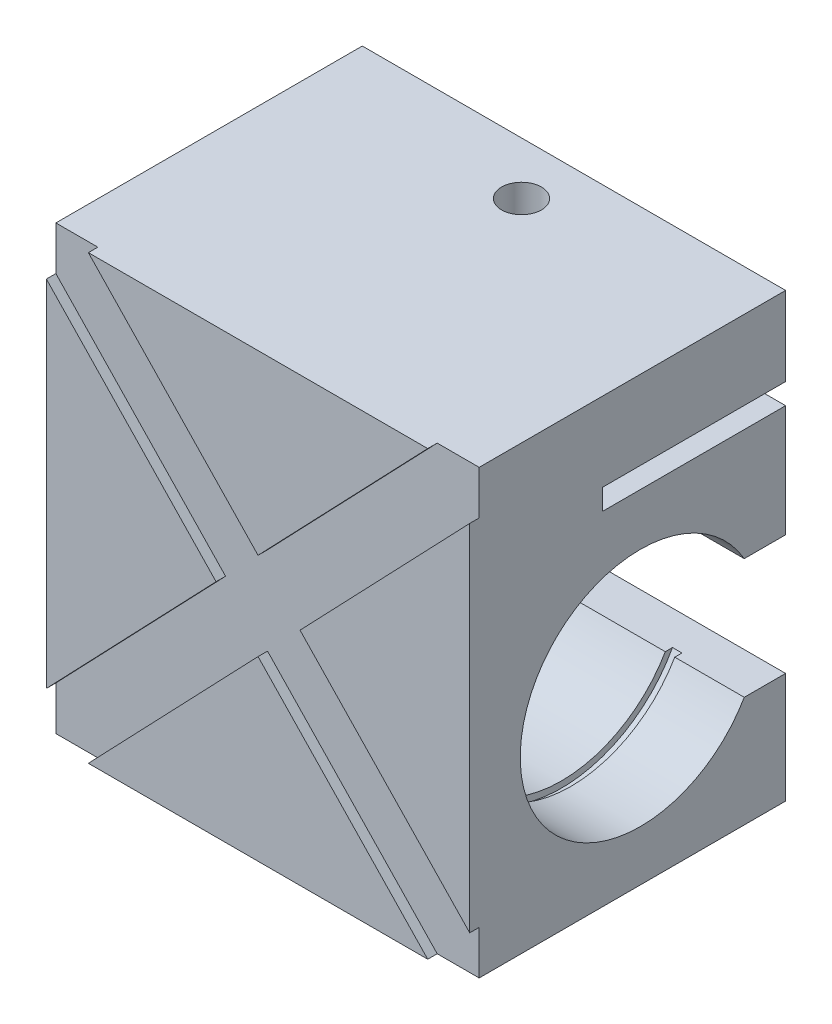
SolidWorks part; units mm, degrees
other "Marquage1"
sketch "Esquisse7" plane through (33.5, 70, 25) normal (0.218, 0.0746, 0.9731) x (0.966, 0.1258, -0.226)
material "AISI 1020"
ref_plane "Plan de face" through (0, 0, 0) normal (0, 0, 1) x (1, 0, 0)
ref_plane "Plan de dessus" through (0, 0, 0) normal (0, 1, 0) x (1, 0, 0)
ref_plane "Plan de droite" through (0, 0, 0) normal (1, 0, 0) x (0, 0, -1)
sketch "Esquisse1" plane through (0, 0, 0) normal (0, 1, 0) x (1, 0, 0)
  line L1 (-33.5, 25) -> (33.5, 25)
  line L2 (-33.5, 25) -> (-33.5, -25)
  line L3 (-33.5, -25) -> (33.5, -25)
  line L4 (33.5, 25) -> (33.5, -25)
  line L5 (-33.5, 25) -> (33.5, -25) construction
  line L6 (-33.5, -25) -> (33.5, 25) construction
  point P0 (0, 0)
  dimension "D1" = 67
  dimension "D2" = 50
extrude "Boss.-Extru.1" add sketch "Esquisse1" along normal blind 70
sketch "Esquisse2" plane through (33.5, 0, 0) normal (1, 0, 0) x (0, 0, -1)
  line L0 (25, 57.5) -> (25, 54.2)
  line L1 (25, 70) -> (25, 0) construction
  line L2 (25, 54.2) -> (-4, 54.2)
  line L3 (-4, 54.2) -> (-4, 57.5)
  line L4 (-4, 57.5) -> (25, 57.5)
  line L5 (-25, 70) -> (25, 70) construction
  line L6 (-25, 70) -> (-25, 0) construction
  line L7 (-25, 0) -> (25, 0) construction
  line L8 (2, 27) -> (25, 27) construction
  line L9 (25, 27) -> (25, 36.5)
  line L10 (25, 36.5) -> (18.4545, 36.5)
  line L11 (25, 27) -> (25, 17.5)
  line L12 (25, 17.5) -> (18.4545, 17.5)
  arc A0 (18.4545, 36.5) -> (18.4545, 17.5) centre (2, 27) ccw
  dimension "D6" = 38
  dimension "D1" = 12.5
  dimension "D2" = 3.3
  dimension "D3" = 29
  dimension "D4" = 27
  dimension "D5" = 27
  dimension "D7" = 19
extrude "Enlèv. mat.-Extru.1" cut sketch "Esquisse2" against normal through all
sketch "Esquisse3" plane through (33.5, 0, 0) normal (1, 0, 0) x (0, 0, -1)
  circle A0 centre (2, 27) radius 20
  dimension "D1" = 40
extrude "Enlèv. mat.-Extru.2" cut sketch "Esquisse3" along normal blind 1.5 from offset 12.5 offset against normal yes
mirror "Symétrie1" about plane through (0, 0, 0) normal (1, 0, 0) of "Enlèv. mat.-Extru.2"
sketch "Esquisse5" plane through (0, 70, 0) normal (0, 1, 0) x (1, 0, 0)
  line L0 (-33.5, 25) -> (-33.5, -25) construction
  line L1 (33.5, 25) -> (-33.5, 25) construction
  circle A0 centre (0, 16.7) radius 3.15
  point P6 (-23.1903, 31.0276)
  dimension "D3" = 6.3
  dimension "D1" = 33.5
  dimension "D2" = 8.3
extrude "Enlèv. mat.-Extru.3" cut sketch "Esquisse5" against normal up to next
sketch "Esquisse6" plane through (0, 0, 25) normal (0, 0, 1) x (1, 0, 0)
  line L1 (-30.0324, -3.319) -> (0, 28.0581)
  line L2 (-36.9676, 3.319) -> (-6.6444, 35)
  line L3 (-36.9676, 3.319) -> (-30.0324, -3.319)
  line L4 (30.0324, 73.319) -> (36.9676, 66.681)
  line L6 (-36.9676, 66.681) -> (-6.6444, 35)
  line L7 (-30.0324, 73.319) -> (0, 41.9419)
  line L8 (-36.9676, 66.681) -> (-30.0324, 73.319)
  line L9 (36.9676, 3.319) -> (30.0324, -3.319)
  line L10 (6.6444, 35) -> (36.9676, 66.681)
  line L14 (0, 41.9419) -> (30.0324, 73.319)
  line L16 (0, 28.0581) -> (30.0324, -3.319)
  line L19 (6.6444, 35) -> (36.9676, 3.319)
extrude "Enlèv. mat.-Extru.4" cut sketch "Esquisse6" against normal blind 1.5
equation "\"A\"= 50"
equation "\"B\"= 70"
equation "\"D2@Esquisse1\"=\"A\""
equation "\"D1@Boss.-Extru.1\"=\"B\""
